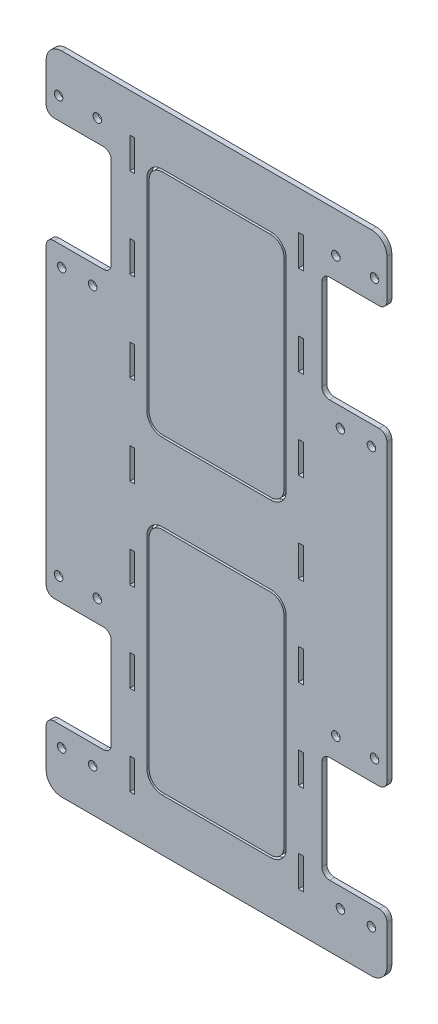
SolidWorks part; units mm, degrees
ref_plane "Plan de face" through (0, 0, 0) normal (0, 0, 1) x (1, 0, 0)
ref_plane "Plan de dessus" through (0, 0, 0) normal (0, 1, 0) x (1, 0, 0)
ref_plane "Plan de droite" through (0, 0, 0) normal (1, 0, 0) x (0, 0, -1)
sketch "Esquisse1" plane through (0, 0, 0) normal (0, 0, 1) x (1, 0, 0)
  line L0 (110, 208.6) -> (-110, 208.6)
  line L1 (-110, 208.6) -> (-110, 168.6)
  line L2 (-110, 168.6) -> (-68, 168.6)
  line L3 (-68, 168.6) -> (-68, 100)
  line L4 (-68, 100) -> (-110, 100)
  line L5 (-110, 100) -> (-110, -100)
  line L6 (-110, -100) -> (-68, -100)
  line L7 (-68, -100) -> (-68, -168.6)
  line L8 (-68, -168.6) -> (-110, -168.6)
  line L9 (-110, -168.6) -> (-110, -208.6)
  line L10 (-110, -208.6) -> (110, -208.6)
  line L11 (110, -208.6) -> (110, -168.6)
  line L12 (110, -168.6) -> (68, -168.6)
  line L13 (68, -168.6) -> (68, -100)
  line L14 (68, -100) -> (110, -100)
  line L15 (110, -100) -> (110, 100)
  line L16 (110, 100) -> (68, 100)
  line L17 (68, 100) -> (68, 168.6)
  line L18 (68, 168.6) -> (110, 168.6)
  line L19 (110, 168.6) -> (110, 208.6)
  point P17 (0, 208.6)
  point P22 (-110, 0)
  point P24 (-110, 188.6)
  dimension "D1" = 68.6
  dimension "D2" = 42
  dimension "D3" = 42
  dimension "D4" = 220
  dimension "D5" = 200
  dimension "D6" = 68.6
  dimension "D8" = 40
  dimension "D7" = 40
  dimension "D9" = 417.2
extrude "Boss.-Extru.1" add sketch "Esquisse1" along normal blind 3.175
sketch "Esquisse2" plane through (0, 0, 3.175) normal (0, 0, 1) x (1, 0, 0)
  line L0 (110, 208.6) -> (-110, 208.6) construction
  line L1 (-56, 183.6) -> (-52.825, 183.6)
  line L2 (-56, 183.6) -> (-56, 163.6)
  line L3 (-56, 163.6) -> (-52.825, 163.6)
  line L4 (-52.825, 183.6) -> (-52.825, 163.6)
  line L9 (-68, 168.6) -> (-68, 100) construction
  line L44 (-56, 125.7333) -> (-56, 105.7333)
  line L45 (-56, 125.7333) -> (-52.825, 125.7333)
  line L46 (-52.825, 125.7333) -> (-52.825, 105.7333)
  line L47 (-56, 105.7333) -> (-52.825, 105.7333)
  line L48 (-56, 67.8667) -> (-56, 47.8667)
  line L49 (-56, 67.8667) -> (-52.825, 67.8667)
  line L50 (-52.825, 67.8667) -> (-52.825, 47.8667)
  line L51 (-56, 47.8667) -> (-52.825, 47.8667)
  line L52 (-56, 10) -> (-56, -10)
  line L53 (-56, 10) -> (-52.825, 10)
  line L54 (-52.825, 10) -> (-52.825, -10)
  line L55 (-56, -10) -> (-52.825, -10)
  line L56 (-56, -47.8667) -> (-56, -67.8667)
  line L57 (-56, -47.8667) -> (-52.825, -47.8667)
  line L58 (-52.825, -47.8667) -> (-52.825, -67.8667)
  line L59 (-56, -67.8667) -> (-52.825, -67.8667)
  line L60 (-56, -105.7333) -> (-56, -125.7333)
  line L61 (-56, -105.7333) -> (-52.825, -105.7333)
  line L62 (-52.825, -105.7333) -> (-52.825, -125.7333)
  line L63 (-56, -125.7333) -> (-52.825, -125.7333)
  line L64 (-56, -163.6) -> (-56, -183.6)
  line L65 (-56, -163.6) -> (-52.825, -163.6)
  line L66 (-52.825, -163.6) -> (-52.825, -183.6)
  line L67 (-56, -183.6) -> (-52.825, -183.6)
  line L69 (-110, -208.6) -> (110, -208.6) construction
  dimension "D1" = 25
  dimension "D2" = 12
  dimension "D3" = 20
  dimension "D6" = 25
  dimension "D4" = 3.175
  dimension "D5" = 7
extrude "Enlèv. mat.-Extru.1" cut sketch "Esquisse2" against normal through all both and the other way through all
mirror "Symétrie1" about plane through (0, 0, 0) normal (1, 0, 0) of "Enlèv. mat.-Extru.1"
hole_wizard "Dégagement M51" positions "Esquisse3D1" profile "Esquisse4" hole size "M5" standard "Ansi Metric" end condition through all
sketch3d "Esquisse3D1"
  line L0 (-110, 168.6, 3.175) -> (-68, 168.6, 3.175) construction
  line L5 (-110, -100, 3.175) -> (-68, -100, 3.175) construction
  line L6 (-110, 208.6, 3.175) -> (-110, 168.6, 3.175) construction
  line L7 (110, 168.6, 3.175) -> (110, 208.6, 3.175) construction
  line L8 (-68, 100, 3.175) -> (-110, 100, 3.175) construction
  line L9 (-110, 100, 3.175) -> (-110, -100, 3.175) construction
  line L10 (110, -100, 3.175) -> (110, 100, 3.175) construction
  line L11 (-68, -168.6, 3.175) -> (-110, -168.6, 3.175) construction
  point P0 (100, -181.1, 3.175)
  point P2 (80, -181.1, 3.175)
  point P4 (-100, -181.1, 3.175)
  point P6 (-80, -181.1, 3.175)
  point P8 (-102, -86, 3.175)
  point P10 (-77, -86, 3.175)
  point P12 (77, -86, 3.175)
  point P14 (102, -86, 3.175)
  point P16 (80, 87.5, 3.175)
  point P22 (100, 87.5, 3.175)
  point P26 (77, 182.6, 3.175)
  point P28 (102, 182.6, 3.175)
  point P30 (-100, 87.5, 3.175)
  point P32 (-80, 87.5, 3.175)
  point P34 (-102, 182.6, 3.175)
  point P36 (-77, 182.6, 3.175)
  dimension "D4" = 25
  dimension "D1" = 14
  dimension "D2" = 25
  dimension "D5" = 14
  dimension "D3" = 8
  dimension "D6" = 8
  dimension "D7" = 12.5
  dimension "D8" = 20
  dimension "D9" = 10
  dimension "D10" = 10
  dimension "D11" = 20
  dimension "D12" = 12.5
sketch "Esquisse4" plane through (100, -181.1, 3.175) normal (1, 0, 0) x (0, -1, 0)
  line L0 (0, 0) -> (0, 3.175)
  line L1 (0, 3.175) -> (2.75, 3.175)
  line L2 (2.75, 3.175) -> (2.75, 0)
  line L5 (2.75, 0) -> (0, 0)
  line L11 (0, -6.35) -> (0, 107.95) construction
  dimension "Diamètre du perçage jusqu'au prochain" = 5.5
  dimension "Profondeur du perçage jusqu'au prochain" = 3.175
fillet "Congé1" radius 5 16 edges at (-110, 168.6, 1.5875) (110, 168.6, 1.5875) (110, 100, 1.5875) (68, 100, 1.5875) (68, 168.6, 1.5875) (68, -100, 1.5875) (110, -168.6, 1.5875) (110, -100, 1.5875) (68, -168.6, 1.5875) (-68, 100, 1.5875) (-68, 168.6, 1.5875) (-68, -100, 1.5875) (-68, -168.6, 1.5875) (-110, -168.6, 1.5875) (-110, -100, 1.5875) (-110, 100, 1.5875)
fillet "Congé2" radius 10 4 edges at (110, -208.6, 1.5875) (-110, -208.6, 1.5875) (-110, 208.6, 1.5875) (110, 208.6, 1.5875)
sketch "Sketch2" plane through (0, 0, 3.175) normal (0, 0, 1) x (1, 0, 0)
  line L0 (0, -1.7463) -> (0, 1.7463) construction
  line L1 (35, 175) -> (-35, 175)
  line L2 (45, 165) -> (45, 35)
  line L3 (35, 25) -> (-35, 25)
  line L4 (-45, 165) -> (-45, 35)
  line L5 (45, 175) -> (-45, 25) construction
  line L6 (45, 25) -> (-45, 175) construction
  line L7 (35, -25) -> (-35, -25)
  line L8 (45, -35) -> (45, -165)
  line L9 (35, -175) -> (-35, -175)
  line L10 (-45, -35) -> (-45, -165)
  line L11 (45, -25) -> (-45, -175) construction
  line L12 (45, -175) -> (-45, -25) construction
  line L13 (1.7463, 0) -> (-1.7463, 0) construction
  arc A0 (35, 175) -> (45, 165) centre (35, 165) cw
  arc A1 (-45, 165) -> (-35, 175) centre (-35, 165) cw
  arc A2 (-45, -165) -> (-35, -175) centre (-35, -165) ccw
  arc A3 (35, -175) -> (45, -165) centre (35, -165) ccw
  arc A4 (-45, -35) -> (-35, -25) centre (-35, -35) cw
  arc A5 (35, -25) -> (45, -35) centre (35, -35) cw
  arc A6 (45, 35) -> (35, 25) centre (35, 35) cw
  arc A7 (-35, 25) -> (-45, 35) centre (-35, 35) cw
  point P0 (0, 100)
  point P5 (0, -100)
  dimension "D5" = 10
  dimension "D6" = 10
  dimension "D7" = 10
  dimension "D1" = 90
  dimension "D2" = 150
  dimension "D3" = 100
  dimension "D4" = 100
split "Split1" trim tools "Sketch2" bodies to split 112 resulting bodies 114 115 116
sketch "Sketch3" plane through (0, 0, 3.175) normal (0, 0, 1) x (1, 0, 0)
  line L24 (43.5, 35) -> (43.5, 165)
  line L25 (35, 173.5) -> (-35, 173.5)
  line L26 (-43.5, 165) -> (-43.5, 35)
  line L27 (-35, 26.5) -> (35, 26.5)
  line L28 (43.5, 35) -> (43.5, 165)
  line L29 (35, 173.5) -> (-35, 173.5)
  line L30 (-43.5, 165) -> (-43.5, 35)
  line L31 (-35, 26.5) -> (35, 26.5)
  line L36 (45, 35) -> (45, 165)
  line L37 (35, 175) -> (-35, 175)
  line L38 (-45, 165) -> (-45, 35)
  line L39 (-35, 25) -> (35, 25)
  line L40 (45, 35) -> (45, 165)
  line L41 (35, 175) -> (-35, 175)
  line L42 (-45, 165) -> (-45, 35)
  line L43 (-35, 25) -> (35, 25)
  arc A24 (43.5, 165) -> (35, 173.5) centre (35, 165) ccw
  arc A25 (-35, 173.5) -> (-43.5, 165) centre (-35, 165) ccw
  arc A26 (-43.5, 35) -> (-35, 26.5) centre (-35, 35) ccw
  arc A27 (35, 26.5) -> (43.5, 35) centre (35, 35) ccw
  arc A28 (43.5, 165) -> (35, 173.5) centre (35, 165) ccw
  arc A29 (-35, 173.5) -> (-43.5, 165) centre (-35, 165) ccw
  arc A30 (-43.5, 35) -> (-35, 26.5) centre (-35, 35) ccw
  arc A31 (35, 26.5) -> (43.5, 35) centre (35, 35) ccw
  arc A36 (45, 165) -> (35, 175) centre (35, 165) ccw
  arc A37 (-35, 175) -> (-45, 165) centre (-35, 165) ccw
  arc A38 (-45, 35) -> (-35, 25) centre (-35, 35) ccw
  arc A39 (35, 25) -> (45, 35) centre (35, 35) ccw
  arc A40 (45, 165) -> (35, 175) centre (35, 165) ccw
  arc A41 (-35, 175) -> (-45, 165) centre (-35, 165) ccw
  arc A42 (-45, 35) -> (-35, 25) centre (-35, 35) ccw
  arc A43 (35, 25) -> (45, 35) centre (35, 35) ccw
  dimension "D1" = 1.5
  dimension "D2" = 0
extrude "Cut-Extrude2" cut sketch "Sketch3" against normal up to next (3.175 mm away) and the other way through all
sketch "Sketch6" plane through (0, 0, 3.175) normal (0, 0, 1) x (1, 0, 0)
  line L0 (-43.5, -35) -> (-43.5, -165)
  line L1 (-35, -173.5) -> (35, -173.5)
  line L2 (43.5, -165) -> (43.5, -35)
  line L3 (35, -26.5) -> (-35, -26.5)
  line L8 (-45, -35) -> (-45, -165)
  line L9 (-35, -175) -> (35, -175)
  line L10 (45, -165) -> (45, -35)
  line L11 (35, -25) -> (-35, -25)
  line L12 (-45, -35) -> (-45, -165)
  line L13 (-35, -175) -> (35, -175)
  line L14 (45, -165) -> (45, -35)
  line L15 (35, -25) -> (-35, -25)
  arc A0 (-43.5, -165) -> (-35, -173.5) centre (-35, -165) ccw
  arc A1 (35, -173.5) -> (43.5, -165) centre (35, -165) ccw
  arc A2 (43.5, -35) -> (35, -26.5) centre (35, -35) ccw
  arc A3 (-35, -26.5) -> (-43.5, -35) centre (-35, -35) ccw
  arc A8 (-45, -165) -> (-35, -175) centre (-35, -165) ccw
  arc A9 (35, -175) -> (45, -165) centre (35, -165) ccw
  arc A10 (45, -35) -> (35, -25) centre (35, -35) ccw
  arc A11 (-35, -25) -> (-45, -35) centre (-35, -35) ccw
  arc A12 (-45, -165) -> (-35, -175) centre (-35, -165) ccw
  arc A13 (35, -175) -> (45, -165) centre (35, -165) ccw
  arc A14 (45, -35) -> (35, -25) centre (35, -35) ccw
  arc A15 (-35, -25) -> (-45, -35) centre (-35, -35) ccw
  dimension "D1" = 0
extrude "Cut-Extrude3" cut sketch "Sketch6" against normal up to next (3.175 mm away)
equation "\"D3@Esquisse1\"=\"D2@Esquisse1\""
equation "\"D6@Esquisse1\"=\"D1@Esquisse1\""
equation "\"D6@Esquisse2\"=\"D1@Esquisse2\""
equation "\"EpaisseurBois\"= 3.175mm"
equation "\"D4@Esquisse3D1\"=\"D2@Esquisse3D1\""
equation "\"D5@Esquisse3D1\"=\"D1@Esquisse3D1\""
equation "\"D6@Esquisse3D1\"=\"D3@Esquisse3D1\""
equation "\"D10@Esquisse3D1\"=\"D9@Esquisse3D1\""
equation "\"D11@Esquisse3D1\"=\"D8@Esquisse3D1\""
equation "\"D12@Esquisse3D1\"=\"D7@Esquisse3D1\""
equation "\"D4@Sketch2\"=\"D3@Sketch2\""
